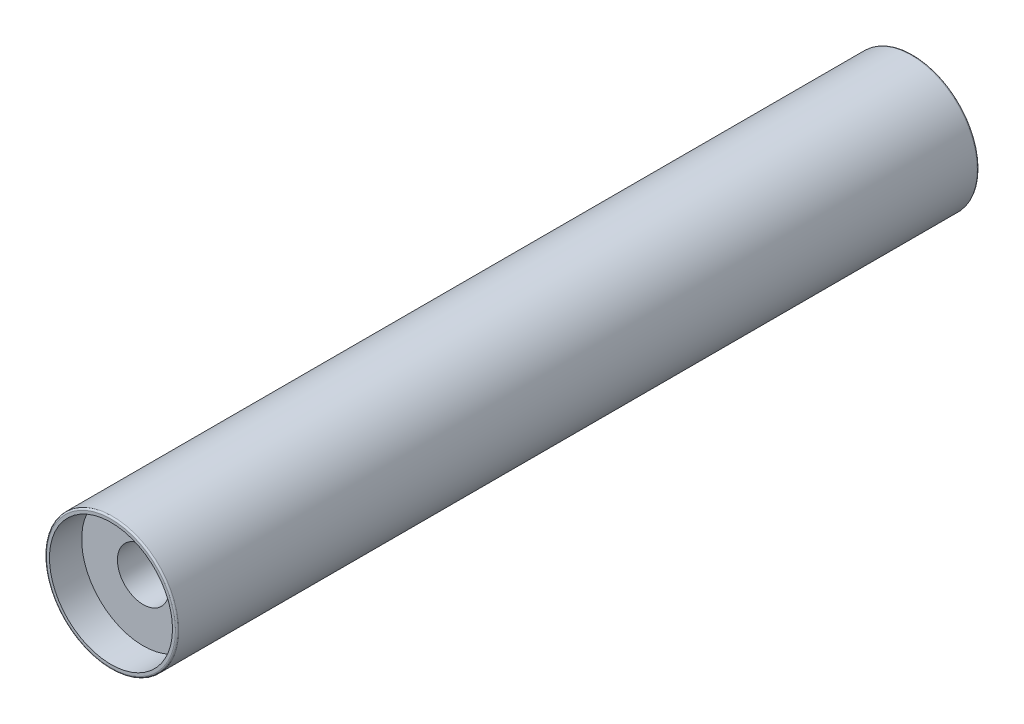
SolidWorks part; units mm, degrees
ref_plane "Plane1" through (0, 0, 0) normal (0, 0, 1) x (1, 0, 0)
ref_plane "Plane2" through (0, 0, 0) normal (0, 1, 0) x (1, 0, 0)
ref_plane "Plane3" through (0, 0, 0) normal (1, 0, 0) x (0, 0, -1)
sketch "Sketch1" plane through (0, 0, 0) normal (0, 0, 1) x (1, 0, 0)
  circle A0 centre (0, 0) radius 10.25
  dimension "D1" = 20.5
extrude "Base-Extrude" add sketch "Sketch1" along normal up to surface (62.2325 mm away) and the other way up to surface (62.2325 mm away)
sketch "Sketch2" plane through (0, 0, 0) normal (0, 0, 1) x (1, 0, 0)
  circle A0 centre (0, 0) radius 9.525
  dimension "D1" = 19.05
extrude "StrokeChamber" cut sketch "Sketch2" along normal up to surface and the other way up to surface
sketch "Sketch3" plane through (0, 0, 0) normal (0, 0, 1) x (1, 0, 0)
  circle A0 centre (0, 0) radius 4
  dimension "D1" = 8
extrude "RodBore" cut sketch "Sketch3" against normal through all and the other way through all
fillet "Fillet1" radius 0.25 2 edges at (10.25, 0, -62.2325) (10.25, 0, 62.2325)
sketch "Sketch4" plane through (0, 0, 62.2325) normal (0, 0, 1) x (1, 0, 0)
  circle A0 centre (0, 0) radius 9.55
  dimension "D1" = 19.1
extrude "Cut-Extrude1" cut sketch "Sketch4" against normal blind 5
mirror "Mirror1" about plane through (0, 0, 0) normal (0, 0, 1) of "Cut-Extrude1"
